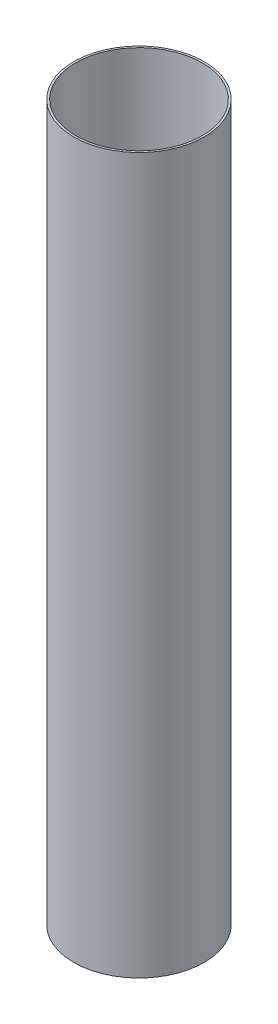
SolidWorks part; units mm, degrees
material "Balsa"
ref_plane "Front Plane" through (0, 0, 0) normal (0, 0, 1) x (1, 0, 0)
ref_plane "Top Plane" through (0, 0, 0) normal (0, 1, 0) x (1, 0, 0)
ref_plane "Right Plane" through (0, 0, 0) normal (1, 0, 0) x (0, 0, -1)
sketch "Sketch1" plane through (0, 0, 0) normal (0, 1, 0) x (1, 0, 0)
  circle A0 centre (0, 0) radius 51.105
  dimension "D1" = 102.21
extrude "Boss-Extrude1" add sketch "Sketch1" along normal blind 560
sketch "Sketch3" plane through (0, 0, 0) normal (0, -1, 0) x (1, 0, 0)
  circle A0 centre (0, 0) radius 49.53
  dimension "D1" = 99.06
extrude "Cut-Extrude1" cut sketch "Sketch3" against normal through all
